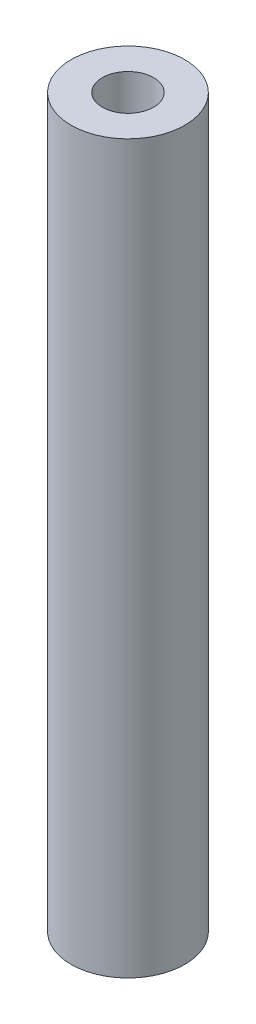
SolidWorks part; units mm, degrees
material "1060 Alloy"
ref_plane "Front Plane" through (0, 0, 0) normal (0, 0, 1) x (1, 0, 0)
ref_plane "Top Plane" through (0, 0, 0) normal (0, 1, 0) x (1, 0, 0)
ref_plane "Right Plane" through (0, 0, 0) normal (1, 0, 0) x (0, 0, -1)
sketch "Sketch1" plane through (0, 0, 0) normal (0, 1, 0) x (1, 0, 0)
  circle A0 centre (0, 0) radius 3
  dimension "D1" = 6
extrude "Boss-Extrude1" add sketch "Sketch1" along normal blind 38.34
hole_wizard "#6-32 Tapped Hole1" positions "Sketch2" profile "Sketch3" tap size "#6-32" standard "ANSI Inch"
sketch "Sketch2" plane through (0, 38.34, 0) normal (0, 1, 0) x (1, 0, 0)
  point P0 (0, 0)
sketch "Sketch3" plane through (0, 38.34, 0) normal (1, 0, 0) x (0, 0, 1)
  line L0 (0, 0) -> (0, 7.8127)
  line L1 (0, 7.8127) -> (1.3525, 7)
  line L2 (1.3525, 7) -> (1.3525, 0)
  line L5 (1.3525, 0) -> (0, 0)
  line L10 (0, 7.8127) -> (-1.3526, 7) construction
  line L11 (0, -6.35) -> (0, 107.95) construction
  dimension "Tap Drill Dia." = 2.7051
  dimension "Tap Drill Depth" = 7
  dimension "Drill Angle" = 118
cosmetic thread "Hole Thread1"
hole_wizard "#6-32 Tapped Hole2" positions "Sketch4" profile "Sketch5" tap size "#6-32" standard "ANSI Inch"
sketch "Sketch4" plane through (0, 0, 0) normal (0, -1, 0) x (-1, 0, 0)
  point P0 (0, 0)
sketch "Sketch5" plane through (0, 0, 0) normal (1, 0, 0) x (0, 0, -1)
  line L0 (0, 0) -> (0, 7.8127)
  line L1 (0, 7.8127) -> (1.3525, 7)
  line L2 (1.3525, 7) -> (1.3525, 0)
  line L5 (1.3525, 0) -> (0, 0)
  line L10 (0, 7.8127) -> (-1.3526, 7) construction
  line L11 (0, -6.35) -> (0, 107.95) construction
  dimension "Tap Drill Dia." = 2.7051
  dimension "Tap Drill Depth" = 7
  dimension "Drill Angle" = 118
cosmetic thread "Hole Thread2"
